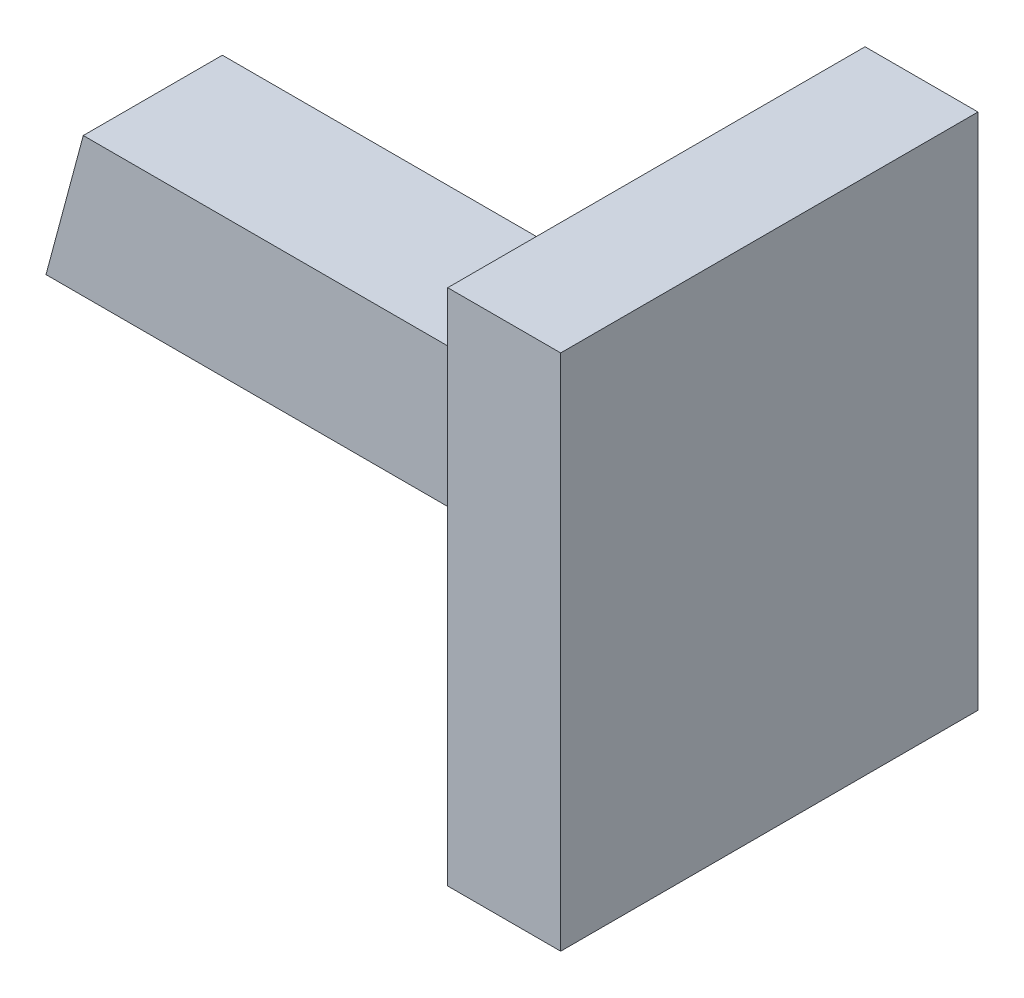
SolidWorks part; units mm, degrees
ref_plane "Front Plane" through (0, 0, 0) normal (0, 0, 1) x (1, 0, 0)
ref_plane "Top Plane" through (0, 0, 0) normal (0, 1, 0) x (1, 0, 0)
ref_plane "Right Plane" through (0, 0, 0) normal (1, 0, 0) x (0, 0, -1)
sketch "Sketch1" plane through (0, 0, 0) normal (0, 0, 1) x (1, 0, 0)
  line L1 (0, 0) -> (47, 0)
  line L2 (0, 0) -> (0, 10)
  line L3 (0, 10) -> (47, 10)
  line L4 (47, 0) -> (47, 10)
  dimension "D1" = 47
  dimension "D2" = 10
extrude "Boss-Extrude1" add sketch "Sketch1" along normal blind 10
ref_plane "Plane1" through (0, 0, 5) normal (0, 0, 1) x (1, 0, 0)
sketch "Sketch5" plane through (0, 0, 5) normal (0, 0, 1) x (1, 0, 0)
  line L0 (47, 10) -> (0, 10) construction
  line L1 (47, -13.625) -> (38.8791, -13.625)
  line L2 (47, -13.625) -> (47, 23.625)
  line L3 (47, 23.625) -> (38.8791, 23.625)
  line L4 (38.8791, -13.625) -> (38.8791, 23.625)
  line L7 (47, 0) -> (47, 10) construction
  dimension "D1" = 13.625
  dimension "D2" = 37.25
  dimension "D3" = 0
extrude "Boss-Extrude3" add sketch "Sketch5" along normal blind 15 and the other way blind 15
sketch "Sketch6" plane through (0, 0, 10) normal (0, 0, 1) x (1, 0, 0)
  line L0 (0, 10) -> (2.6795, 10)
  line L1 (38.8791, 10) -> (0, 10) construction
  line L2 (2.6795, 10) -> (0, 0)
  line L3 (0, 0) -> (0, 10)
  dimension "D1" = 75
extrude "Cut-Extrude1" cut sketch "Sketch6" against normal through all
